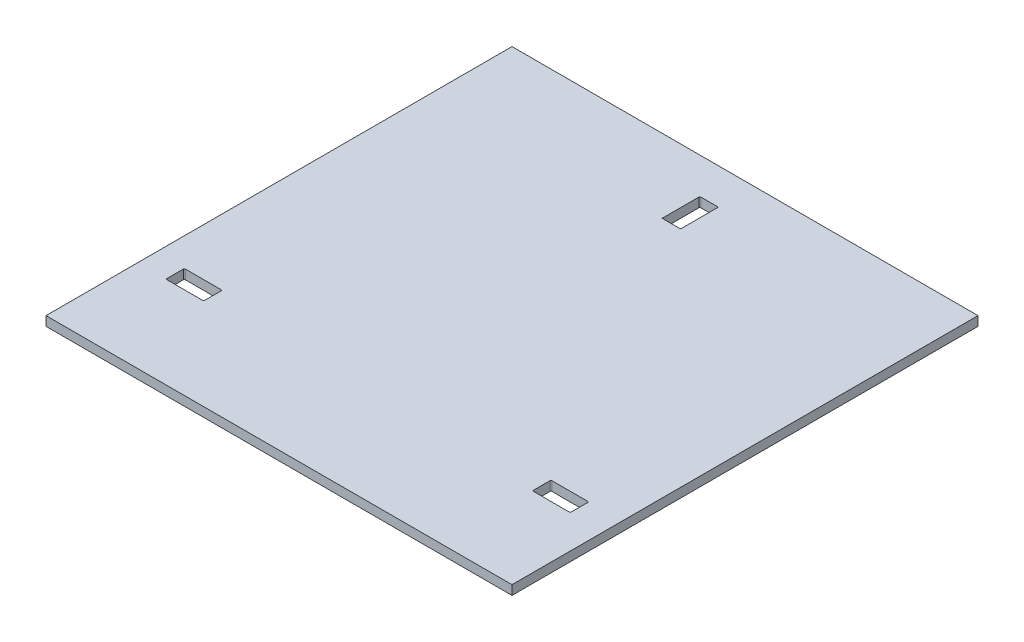
SolidWorks part; units mm, degrees
ref_plane "Alzado" through (0, 0, 0) normal (0, 0, 1) x (1, 0, 0)
ref_plane "Planta" through (0, 0, 0) normal (0, 1, 0) x (1, 0, 0)
ref_plane "Vista lateral" through (0, 0, 0) normal (1, 0, 0) x (0, 0, -1)
sketch "Croquis1" plane through (0, 0, 0) normal (0, 1, 0) x (1, 0, 0)
  line L1 (0, 0) -> (500, 0)
  line L2 (0, 0) -> (0, 500)
  line L3 (0, 500) -> (500, 500)
  line L4 (500, 0) -> (500, 500)
extrude "Saliente-Extruir1" add sketch "Croquis1" along normal blind 10
sketch "Croquis12" plane through (0, 0, 0) normal (0, -1, 0) x (-1, 0, 0)
  line L0 (-250, 218.1227) -> (-250, 438.1227) construction
  line L1 (-250, 438.1227) -> (-59.4744, 108.1227) construction
  line L2 (-59.4744, 108.1227) -> (-250, 218.1227) construction
  line L3 (-250, 218.1227) -> (-440.5256, 108.1227) construction
  line L4 (-440.5256, 108.1227) -> (-250, 438.1227) construction
  line L5 (-59.4744, 108.1227) -> (-440.5256, 108.1227) construction
sketch "Croquis22" plane through (0, 10, 0) normal (0, 1, 0) x (1, 0, 0)
  line L0 (250, 438.1227) -> (59.4744, 108.1227) construction
  line L1 (30.422, 118.0227) -> (70.922, 118.0227)
  line L2 (30.422, 118.0227) -> (30.422, 98.2227)
  line L3 (30.422, 98.2227) -> (70.922, 98.2227)
  line L4 (70.922, 118.0227) -> (70.922, 98.2227)
  line L5 (423.7714, 98.2227) -> (464.2714, 98.2227)
  line L6 (423.7714, 98.2227) -> (423.7714, 118.0227)
  line L7 (423.7714, 118.0227) -> (464.2714, 118.0227)
  line L8 (464.2714, 98.2227) -> (464.2714, 118.0227)
  line L9 (240.1, 420.9754) -> (259.9, 420.9754)
  line L10 (240.1, 420.9754) -> (240.1, 461.4754)
  line L11 (240.1, 461.4754) -> (259.9, 461.4754)
  line L12 (259.9, 420.9754) -> (259.9, 461.4754)
  line L13 (250, 218.1227) -> (250, 438.1227) construction
  line L14 (59.4744, 108.1227) -> (440.5256, 108.1227) construction
  dimension "D1" = 40.5
  dimension "D2" = 19.8
  dimension "D3" = 40.5
  dimension "D4" = 19.8
  dimension "D5" = 40.5
  dimension "D6" = 9.9
  dimension "D7" = 19.8
  dimension "D8" = 9.9
  dimension "D9" = 9.9
extrude "Cortar-Extruir1" cut sketch "Croquis22" against normal blind 10
fillet "Redondeo1" radius 1 11 edges at (423.7714, 5, -98.2227) (30.422, 5, -98.2227) (70.922, 5, -98.2227) (464.2714, 5, -98.2227) (259.9, 5, -420.9754) (70.922, 5, -118.0227) (259.9, 5, -461.4754) (464.2714, 5, -118.0227) (423.7714, 5, -118.0227) (240.1, 5, -461.4754) (30.422, 5, -118.0227)
